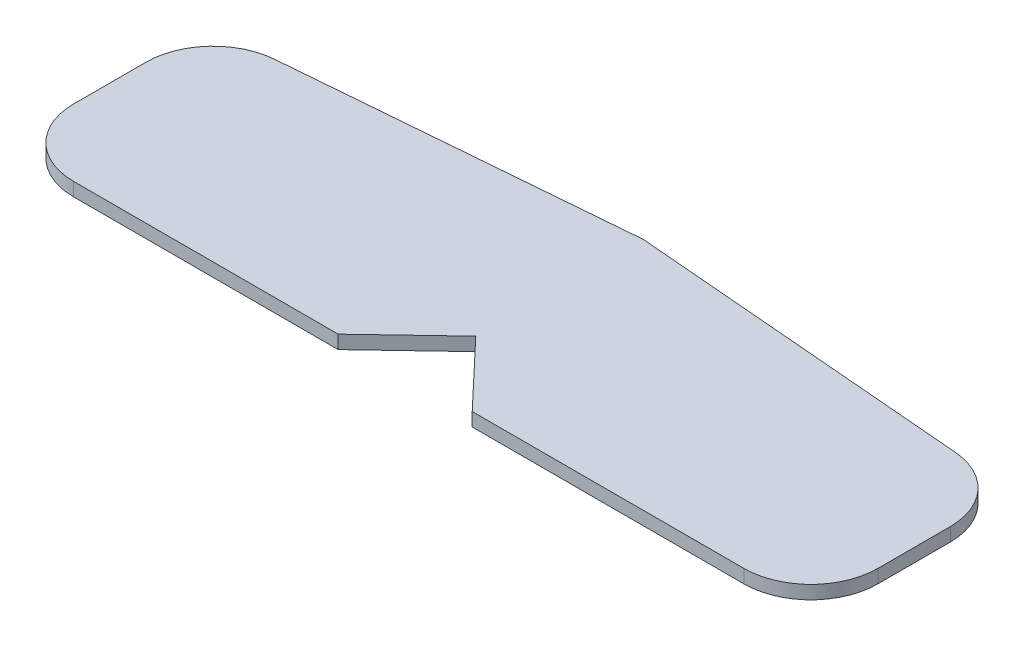
SolidWorks part; units mm, degrees
ref_plane "Front Plane" through (0, 0, 0) normal (0, 0, 1) x (1, 0, 0)
ref_plane "Top Plane" through (0, 0, 0) normal (0, 1, 0) x (1, 0, 0)
ref_plane "Right Plane" through (0, 0, 0) normal (1, 0, 0) x (0, 0, -1)
sketch "Sketch1" plane through (0, 0, 0) normal (0, 1, 0) x (1, 0, 0)
  line L0 (-50.8305, 13.2641) -> (0, 17.5)
  line L1 (-50, -17.5) -> (-10.529, -17.5)
  line L2 (-60, -7.5) -> (-60, 3.2987)
  line L4 (60, -7.5) -> (60, 3.2987)
  line L5 (-60, -17.5) -> (46.6667, 13.6111) construction
  line L6 (-46.6667, 13.6111) -> (60, -17.5) construction
  line L7 (0, 17.5) -> (50.8305, 13.2641)
  line L8 (-10.529, -17.5) -> (0, -7.5)
  line L9 (0, -7.5) -> (9.471, -17.5)
  line L11 (9.471, -17.5) -> (50, -17.5)
  arc A0 (50.8305, 13.2641) -> (60, 3.2987) centre (50, 3.2987) cw
  arc A1 (50, -17.5) -> (60, -7.5) centre (50, -7.5) ccw
  arc A2 (-50, -17.5) -> (-60, -7.5) centre (-50, -7.5) cw
  arc A3 (-50.8305, 13.2641) -> (-60, 3.2987) centre (-50, 3.2987) ccw
  point P0 (0, 0)
  dimension "D3" = 10
  dimension "D1" = 20
  dimension "D2" = 120
extrude "Boss-Extrude1" add sketch "Sketch1" along normal blind 2
